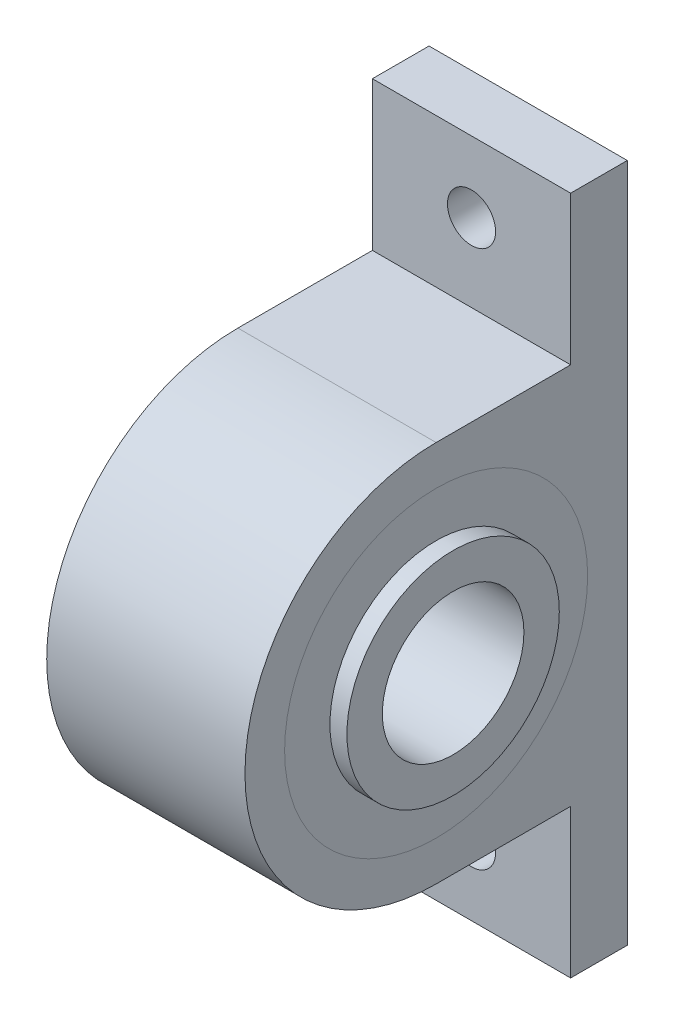
SolidWorks part; units mm, degrees
ref_plane "Front Plane" through (0, 0, 0) normal (0, 0, 1) x (1, 0, 0)
ref_plane "Top Plane" through (0, 0, 0) normal (0, 1, 0) x (1, 0, 0)
ref_plane "Right Plane" through (0, 0, 0) normal (1, 0, 0) x (0, 0, -1)
sketch "Sketch1" plane through (0, 0, 0) normal (0, 0, 1) x (1, 0, 0)
  line L1 (-35, -120) -> (35, -120)
  line L2 (-35, -120) -> (-35, 120)
  line L3 (-35, 120) -> (35, 120)
  line L4 (35, -120) -> (35, 120)
  line L5 (-35, -120) -> (35, 120) construction
  line L6 (-35, 120) -> (35, -120) construction
  point P0 (0, 0)
extrude "Boss-Extrude1" add sketch "Sketch1" along normal blind 20
sketch "Sketch2" plane through (0, 0, 0) normal (1, 0, 0) x (0, 0, -1)
  circle A0 centre (-67.5, 0) radius 67.5
extrude "Boss-Extrude2" add sketch "Sketch2" along normal up to surface and the other way up to surface up to face at (35, 0, 10) other way up to face at (-35, 0, 10)
sketch "Sketch3" plane through (0, 0, 0) normal (1, 0, 0) x (0, 0, -1)
  line L0 (-20, 47.9583) -> (-20, 120) construction
  line L1 (-20, -120) -> (-20, -47.9583) construction
  line L2 (-20, 47.9583) -> (-20, 67.5)
  line L3 (-20, -67.5) -> (-20, -47.9583)
  line L4 (-67.5, 67.5) -> (-20, 67.5)
  line L5 (-67.5, -67.5) -> (-20, -67.5)
  arc A0 (-20, 47.9583) -> (-20, -47.9583) centre (-67.5, 0) ccw construction
  arc A1 (-20, 47.9583) -> (-20, -47.9583) centre (-67.5, 0) ccw
extrude "Boss-Extrude3" add sketch "Sketch3" along normal up to surface and the other way up to surface contours A1 L5 L3 | A1 L2 L4 up to face at (35, 0, 32.5) other way up to face at (-35, 0, 32.5)
sketch "Sketch4" plane through (35, 0, 0) normal (1, 0, 0) x (0, 0, -1)
  circle A1 centre (-67.5, 0) radius 53.5
extrude "Cut-Extrude1" cut sketch "Sketch4" against normal blind 216
sketch "Sketch5" plane through (35, 0, 0) normal (1, 0, 0) x (0, 0, -1)
  circle A0 centre (-67.5, 0) radius 53.5 construction
  circle A1 centre (-67.5, 0) radius 53.5
  circle A2 centre (-67.5, 0) radius 37.5
extrude "Boss-Extrude4" add sketch "Sketch5" against normal up to surface (70 mm away) separate body up to face at (-35, 0, 14)
sketch "Sketch6" plane through (0, 0, 0) normal (1, 0, 0) x (0, 0, -1)
  circle A0 centre (-67.5, 0) radius 25
  circle A1 centre (-67.5, 0) radius 37.5 construction
  circle A2 centre (-67.5, 0) radius 37.5
  dimension "D1" = 50
extrude "Boss-Extrude6" add sketch "Sketch6" along normal blind 41 and the other way blind 45 separate body contours A0
ref_plane "Plane1" through (0, 0, 20) normal (0, 0, 1) x (1, 0, 0)
sketch "Sketch7" plane through (0, 0, 20) normal (0, 0, 1) x (1, 0, 0)
  circle A0 centre (0, -95) radius 8.5
  circle A1 centre (0, 95) radius 8.5
extrude "Cut-Extrude2" cut sketch "Sketch7" against normal blind 58
